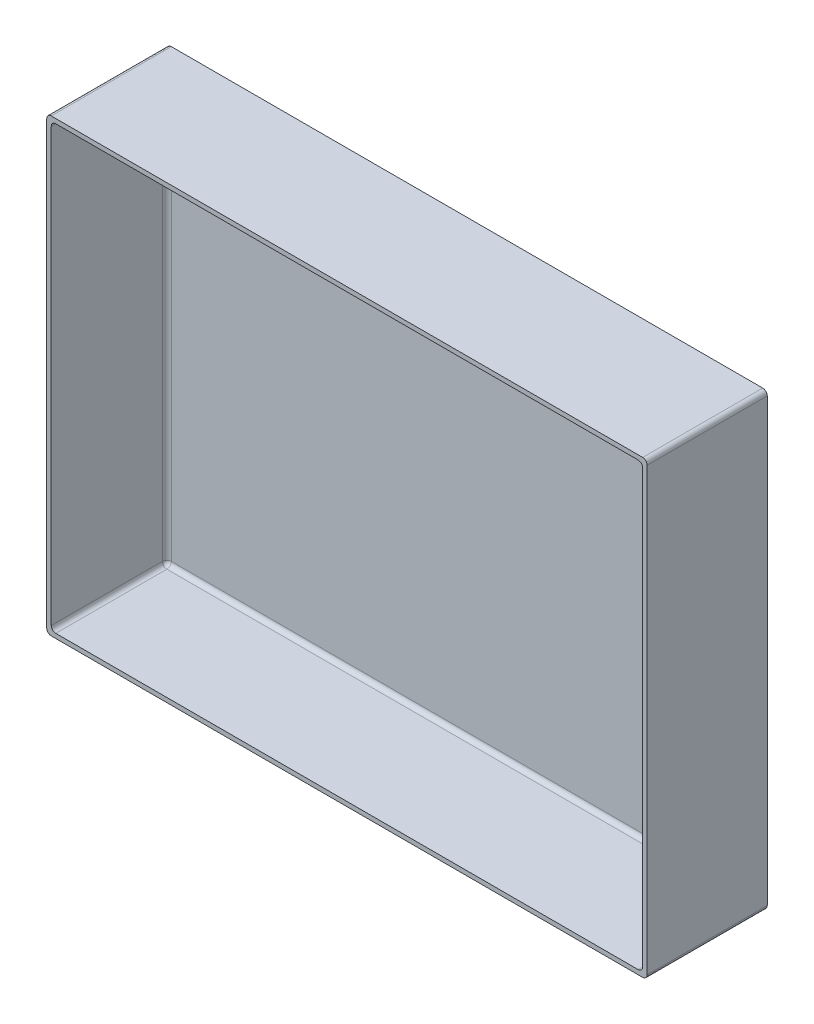
SolidWorks part; units mm, degrees
material "6061 合金"
ref_plane "前视基准面" through (0, 0, 0) normal (0, 0, 1) x (1, 0, 0)
ref_plane "上视基准面" through (0, 0, 0) normal (0, 1, 0) x (1, 0, 0)
ref_plane "右视基准面" through (0, 0, 0) normal (1, 0, 0) x (0, 0, -1)
sketch "草图1" plane through (0, 0, 0) normal (0, 0, 1) x (1, 0, 0)
  line L1 (-200, -150) -> (200, -150)
  line L2 (-200, -150) -> (-200, 150)
  line L3 (-200, 150) -> (200, 150)
  line L4 (200, -150) -> (200, 150)
  line L5 (-200, -150) -> (200, 150) construction
  line L6 (-200, 150) -> (200, -150) construction
  point P0 (0, 0)
  dimension "D1" = 400
  dimension "D2" = 300
extrude "凸台-拉伸1" add sketch "草图1" along normal blind 80
shell "抽壳1" thickness 3
fillet "圆角1" radius 3 8 edges at (197, 0, 3) (0, 147, 3) (0, -147, 3) (197, -147, 41.5) (-197, -147, 41.5) (-197, 147, 41.5) (197, 147, 41.5) (-197, 0, 3)
fillet "圆角2" radius 3 4 edges at (200, -150, 40) (-200, 150, 40) (200, 150, 40) (-200, -150, 40)
